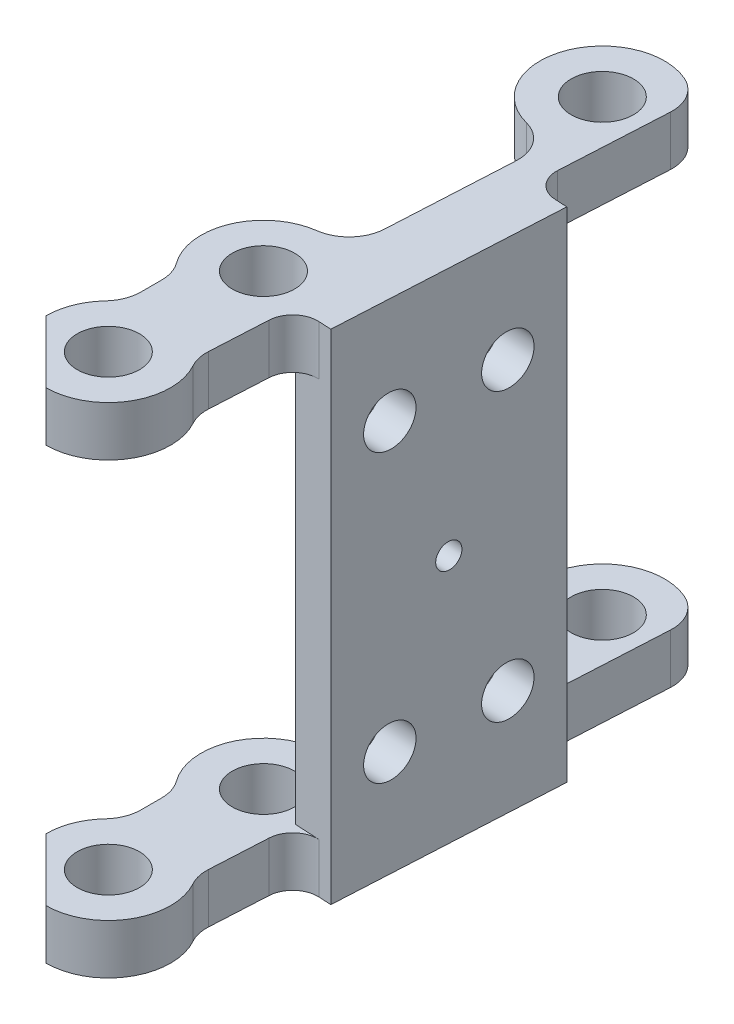
SolidWorks part; units mm, degrees
ref_plane "Front Plane" through (0, 0, 0) normal (0, 0, 1) x (1, 0, 0)
ref_plane "Top Plane" through (0, 0, 0) normal (0, 1, 0) x (1, 0, 0)
ref_plane "Right Plane" through (0, 0, 0) normal (1, 0, 0) x (0, 0, -1)
sketch "Sketch1" plane through (0, 0, 0) normal (0, 1, 0) x (1, 0, 0)
  line L0 (143.3333, 493) -> (716.6667, 493) construction
sketch "Sketch2" plane through (0, 0, 0) normal (0, 1, 0) x (1, 0, 0)
  line L0 (81.4722, 69.2986) -> (86.4722, 64.2986)
  line L1 (83.6263, 73.4096) -> (83.6263, 77.5229)
  line L2 (89.7299, 102.0349) -> (88.8636, 85.8025)
  line L7 (92.4509, 110.0003) -> (90.4247, 72.3609)
  line L8 (92.0481, 102.5189) -> (94.5466, 102.5189)
  line L9 (68.622, 64.6679) -> (68.8091, 64.6679)
  line L10 (82.0956, 50.9646) -> (82.0324, 51.0811)
  line L12 (94.5466, 102.5189) -> (93.4489, 82.1265)
  line L13 (94.0355, 93.0228) -> (93.4252, 81.6866)
  line L14 (93.4252, 81.6866) -> (90.9267, 81.6866)
  line L15 (47.4708, 107.3244) -> (47.5459, 107.4406)
  line L16 (50.5974, 103.1038) -> (50.7762, 103.3805)
  circle A0 centre (86.4722, 69.2986) radius 2.5
  arc A9 (88.8636, 85.8025) -> (83.6263, 77.5229) centre (87.0921, 81.1269) ccw
  arc A10 (83.6263, 73.4096) -> (81.4722, 69.2986) centre (86.4722, 69.2986) ccw
  arc A13 (92.4509, 110.0003) -> (89.7266, 101.9713) centre (88.5782, 106.8376) ccw
  arc A14 (86.4722, 64.2986) -> (90.4247, 72.3609) centre (86.4722, 69.2986) ccw
  circle A15 centre (87.0921, 81.1269) radius 2.5
  circle A18 centre (88.5782, 106.8376) radius 2.5
extrude "Boss-Extrude3" add sketch "Sketch2" along normal blind 4
sketch "Sketch3" plane through (0, 4, 0) normal (0, 1, 0) x (1, 0, 0)
  line L0 (91.801, 97.9276) -> (90.8334, 79.9536)
  line L1 (91.801, 97.9276) -> (94.801, 97.7661)
  line L2 (90.8334, 79.9536) -> (93.8334, 79.7922)
  line L3 (94.801, 97.7661) -> (93.8334, 79.7922)
  line L4 (92.4509, 110.0003) -> (90.4247, 72.3609) construction
  dimension "D1" = 3
  dimension "D2" = 18
extrude "Boss-Extrude4" add sketch "Sketch3" against normal blind 40
ref_plane "Plane1" through (0, -16, 0) normal (0, 1, 0) x (1, 0, 0)
mirror "Mirror1" about plane through (0, -16, 0) normal (0, 1, 0) of "Boss-Extrude3"
fillet "Fillet1" radius 2 4 edges at (90.8334, -34, -79.9536) (90.8334, 2, -79.9536) (91.801, -34, -97.9276) (91.801, 2, -97.9276)
sketch "Sketch4" plane through (86.2794, 0, 4.6445) normal (-0.9986, 0, -0.0538) x (-0.0538, 0, 0.9986)
  line L0 (-84.7207, 0) -> (-89.2207, 0) construction
  line L1 (-102.7207, 0) -> (-84.7207, 0) construction
  line L2 (-89.2207, 0) -> (-89.2207, -4.5) construction
  line L3 (-93.7207, 0) -> (-93.7207, -7.4232) construction
  line L4 (-102.7207, -16) -> (-84.7207, -16) construction
  line L6 (-102.7207, -32) -> (-102.7207, 0) construction
  line L7 (-84.7207, -32) -> (-84.7207, 0) construction
  circle A0 centre (-89.2207, -4.5) radius 2
  circle A1 centre (-98.2207, -4.5) radius 2
  circle A2 centre (-89.2207, -27.5) radius 2
  circle A3 centre (-98.2207, -27.5) radius 2
  circle A4 centre (-93.7207, -16) radius 1
extrude "Cut-Extrude1" cut sketch "Sketch4" against normal blind 10
fillet "Fillet3" radius 3 10 edges at (92.4509, -34, -110.0003) (92.4509, 2, -110.0003) (90.4247, -34, -72.3609) (90.4247, 2, -72.3609) (89.7266, -34, -101.9713) (89.7266, 2, -101.9713) (83.6263, 2, -73.4096) (83.6263, 2, -77.5229) (83.6263, -34, -73.4096) (83.6263, -34, -77.5229)
fillet "Fillet4" radius 3 2 edges at (88.8636, -34, -85.8025) (88.8636, 2, -85.8025)
